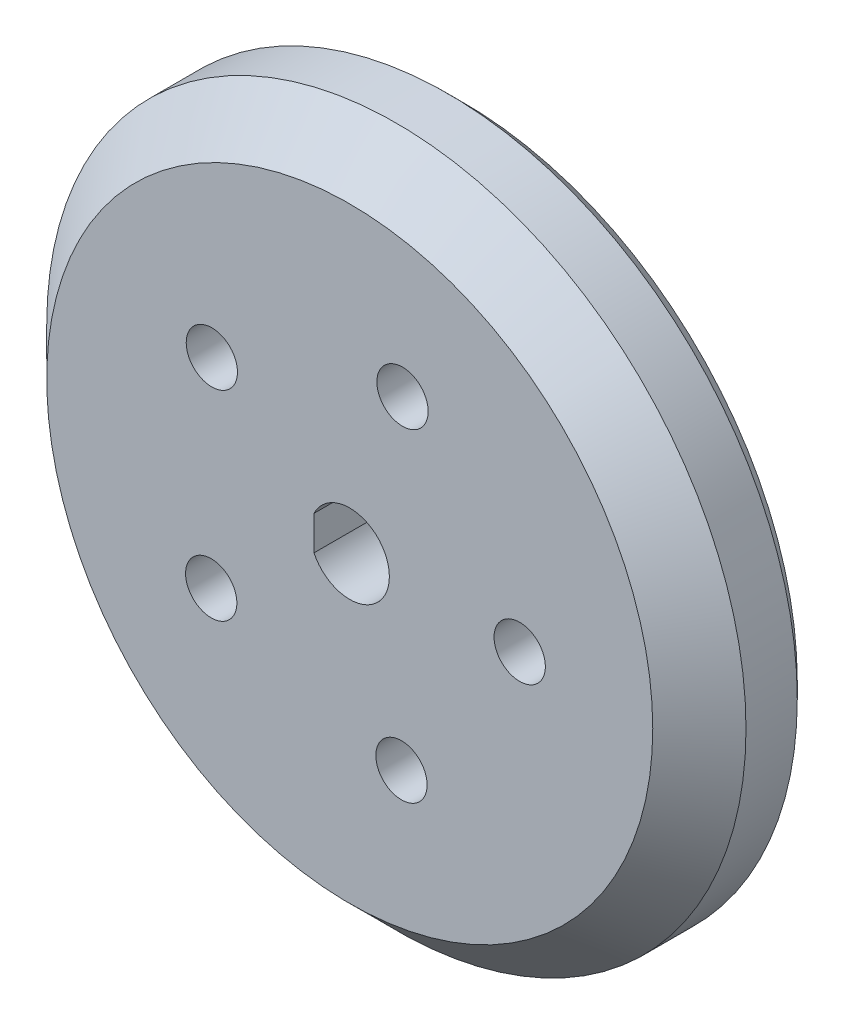
SolidWorks part; units mm, degrees
ref_plane "Front Plane" through (0, 0, 0) normal (0, 0, 1) x (1, 0, 0)
ref_plane "Top Plane" through (0, 0, 0) normal (0, 1, 0) x (1, 0, 0)
ref_plane "Right Plane" through (0, 0, 0) normal (1, 0, 0) x (0, 0, -1)
sketch "Sketch1" plane through (0, 0, 0) normal (0, 0, 1) x (1, 0, 0)
  circle A0 centre (0, 0) radius 22.5
  circle A1 centre (0, 0) radius 2.55
  dimension "D1" = 45
  dimension "D2" = 5.1
extrude "Boss-Extrude1" add sketch "Sketch1" along normal blind 7.3
sketch "Sketch2" plane through (0, 0, 0) normal (0, 0, -1) x (-1, 0, 0)
  line L0 (0, 0) -> (-18.85, 0) construction
  line L1 (0, 0) -> (-5.825, 17.9274) construction
  line L2 (0, 0) -> (15.25, 11.0798) construction
  line L3 (0, 0) -> (15.25, -11.0798) construction
  line L4 (0, 0) -> (-5.825, -17.9274) construction
  line L5 (-22.5, 0) -> (-20.375, 0) construction
  circle A0 centre (-18.85, 0) radius 5.5 construction
  circle A3 centre (-18.85, 0) radius 1.525
  circle A4 centre (-5.825, 17.9274) radius 5.5 construction
  circle A5 centre (-5.825, 17.9274) radius 1.525
  circle A6 centre (15.25, 11.0798) radius 5.5 construction
  circle A7 centre (15.25, 11.0798) radius 1.525
  circle A8 centre (15.25, -11.0798) radius 5.5 construction
  circle A9 centre (15.25, -11.0798) radius 1.525
  circle A10 centre (-5.825, -17.9274) radius 5.5 construction
  circle A11 centre (-5.825, -17.9274) radius 1.525
  circle A13 centre (0, 0) radius 22.5 construction
  point P24 (0, 0)
  dimension "D1" = 11
  dimension "D2" = 3.65
  dimension "D3" = 3.05
  dimension "D4" = 5
extrude "Cut-Extrude1" cut sketch "Sketch2" against normal blind 3.4
sketch "Sketch3" plane through (0, 0, 0) normal (0, 0, -1) x (-1, 0, 0)
  line L3 (-10.9375, 0) -> (-8.55, 0) construction
  line L4 (-10.9375, 0) -> (-13.325, 0) construction
  circle A0 centre (0, 0) radius 8.55 construction
  circle A1 centre (0, 0) radius 2.55 construction
  circle A2 centre (0, 0) radius 2.55
  circle A3 centre (-18.85, 0) radius 5.525 construction
  circle A4 centre (-18.85, 0) radius 1.525 construction
  circle A6 centre (-10.9375, 0) radius 1.65
  circle A7 centre (-3.3953, 10.4497) radius 1.65
  circle A8 centre (8.8736, 6.5058) radius 1.65
  circle A9 centre (8.9141, -6.3813) radius 1.65
  circle A10 centre (-3.3299, -10.4022) radius 1.65
  point P27 (0.025, 0.0344)
  dimension "D1" = 6
  dimension "D2" = 4
  dimension "D3" = 3.3
extrude "Cut-Extrude2" cut sketch "Sketch3" against normal through all both and the other way through all
chamfer "Chamfer7" distance 1 angle 45 1 edges at (22.5, 0, 0)
chamfer "Chamfer8" distance 3 angle 45 1 edges at (22.5, 0, 7.3)
sketch "Sketch8" plane through (0, 0, 0) normal (0, 0, -1) x (-1, 0, 0)
  line L0 (-5.65, -6.5498) -> (-5.65, 6.5498)
  line L1 (-5.65, 0) -> (-8.65, 0) construction
  arc A0 (-5.65, -6.5498) -> (-5.65, 6.5498) centre (0, 0) ccw
  circle A1 centre (0, 0) radius 2.55 construction
  arc A2 (-8.65, 0) -> (-5.65, -6.5498) centre (0, 0) ccw construction
  arc A3 (-5.65, 6.5498) -> (-8.65, 0) centre (0, 0) ccw construction
  dimension "D1" = 6.1
  dimension "D2" = 3
extrude "Cut-Extrude3" cut sketch "Sketch8" against normal blind 2
sketch "Sketch10" plane through (0, 0, 7.3) normal (0, 0, 1) x (1, 0, 0)
  line L0 (2.55, 0) -> (-2.3, 0) construction
  line L1 (-2.3, -1.1011) -> (-2.3, 1.1011)
  circle A0 centre (0, 0) radius 2.55 construction
  arc A1 (-2.3, 1.1011) -> (-2.3, -1.1011) centre (0, 0) ccw
  dimension "D1" = 4.85
extrude "Boss-Extrude2" add sketch "Sketch10" against normal up to surface (5.3 mm away) up to face at (-2.55, 0, 2)
sketch "Croquis1" plane through (0, 0, 7.3) normal (0, 0, 1) x (1, 0, 0)
  line L0 (-2.3, -1.1011) -> (-2.3, 1.1011) construction
  line L1 (-2.3, -1.1011) -> (-2.3, 1.1011)
  arc A0 (-2.3, -1.1011) -> (-2.3, 1.1011) centre (0, 0) ccw construction
  arc A1 (-2.3, -1.1011) -> (-2.3, 1.1011) centre (0, 0) ccw
extrude "Saliente-Extruir1" [suppressed] add sketch "Croquis1" against normal blind 2.6
